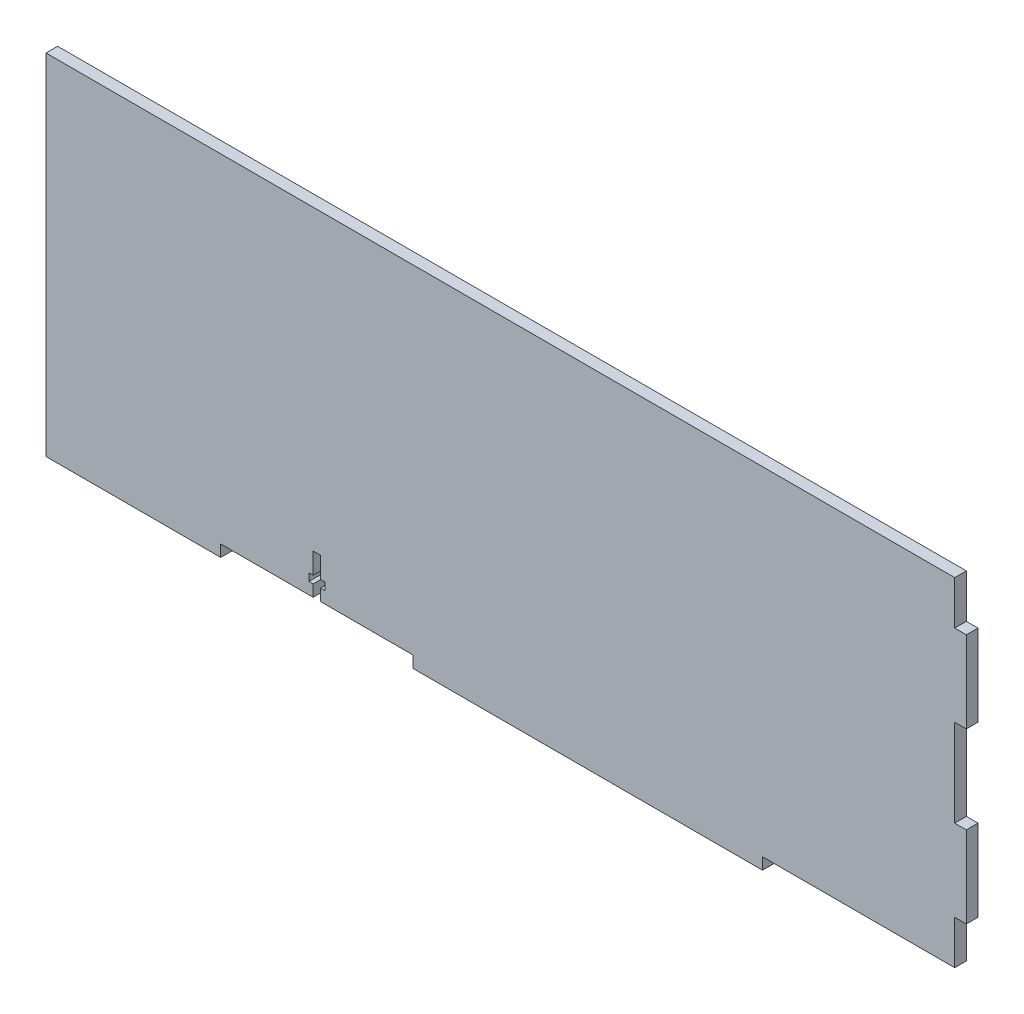
SolidWorks part; units mm, degrees
ref_plane "Alzado" through (0, 0, 0) normal (0, 0, 1) x (1, 0, 0)
ref_plane "Planta" through (0, 0, 0) normal (0, 1, 0) x (1, 0, 0)
ref_plane "Vista lateral" through (0, 0, 0) normal (1, 0, 0) x (0, 0, -1)
sketch "Croquis1" plane through (0, 0, 0) normal (0, 0, 1) x (1, 0, 0)
  line L0 (390, 0) -> (390, -116.2557) construction
  line L1 (0, 0) -> (780, 0)
  line L2 (0, 0) -> (0, 145)
  line L3 (0, 145) -> (780, 145)
  line L4 (780, 0) -> (780, 145)
  line L5 (0, 72.5) -> (-47.1531, 72.5) construction
  line L6 (0, 53.75) -> (-5, 53.75)
  line L7 (0, 126.25) -> (-5, 126.25)
  line L8 (0, 126.25) -> (0, 91.25)
  line L9 (0, 91.25) -> (-5, 91.25)
  line L10 (-5, 126.25) -> (-5, 91.25)
  line L11 (-5, 18.75) -> (-5, 53.75)
  line L12 (0, 18.75) -> (-5, 18.75)
  line L13 (0, 18.75) -> (0, 53.75)
  line L14 (780, 18.75) -> (780, 53.75)
  line L15 (780, 18.75) -> (785, 18.75)
  line L16 (785, 18.75) -> (785, 53.75)
  line L17 (780, 53.75) -> (785, 53.75)
  line L18 (780, 91.25) -> (785, 91.25)
  line L19 (785, 126.25) -> (785, 91.25)
  line L20 (780, 126.25) -> (785, 126.25)
  line L21 (780, 126.25) -> (780, 91.25)
  line L22 (390, 0) -> (315, 0)
  line L27 (82.5, 0) -> (232.5, 0)
  line L28 (82.5, 0) -> (82.5, -5)
  line L29 (82.5, -5) -> (232.5, -5)
  line L30 (232.5, 0) -> (232.5, -5)
  line L31 (315, 0) -> (315, -5)
  line L36 (315, -5) -> (465, -5)
  line L37 (465, -5) -> (465, 0)
  line L38 (465, 0) -> (390, 0)
  line L39 (697.5, -5) -> (547.5, -5)
  line L40 (547.5, 0) -> (547.5, -5)
  line L41 (697.5, 0) -> (547.5, 0)
  line L42 (697.5, 0) -> (697.5, -5)
  dimension "D1" = 780
  dimension "D2" = 145
  dimension "D3" = 18.75
  dimension "D4" = 35
  dimension "D5" = 5
  dimension "D6" = 75
  dimension "D7" = 150
  dimension "D8" = 82.5
  dimension "D9" = 150
  dimension "D10" = 5
  dimension "D11" = 5
extrude "Saliente-Extruir1" add sketch "Croquis1" along normal blind 5 contours L1 L4 L3 L2 | L42 L1 L40 L39 | L36 L37 L1 L31 | L30 L1 L28 L29 | L12 L2 L6 L11 | L16 L17 L14 L15 | L19 L18 L21 L20 | L10 L9 L8 L7
sketch "Croquis2" plane through (0, 0, 5) normal (0, 0, 1) x (1, 0, 0)
  line L0 (273.75, 0) -> (273.75, 79.0587) construction
  line L1 (232.5, 0) -> (315, 0) construction
  line L2 (390, -5) -> (390, 84.2504) construction
  line L3 (315, -5) -> (465, -5) construction
  line L4 (275.35, 0) -> (272.15, 0)
  line L5 (272.15, 0) -> (272.15, 5)
  line L6 (272.15, 5) -> (270.35, 5)
  line L7 (270.35, 5) -> (270.35, 8.2)
  line L8 (270.35, 8.2) -> (272.15, 8.2)
  line L9 (272.15, 8.2) -> (272.15, 17.2)
  line L10 (272.15, 17.2) -> (275.35, 17.2)
  line L11 (275.35, 8.2) -> (275.35, 17.2)
  line L12 (277.15, 8.2) -> (275.35, 8.2)
  line L13 (277.15, 5) -> (277.15, 8.2)
  line L14 (275.35, 5) -> (277.15, 5)
  line L15 (275.35, 0) -> (275.35, 5)
  line L16 (507.85, 8.2) -> (507.85, 17.2)
  line L17 (509.65, 8.2) -> (507.85, 8.2)
  line L18 (509.65, 5) -> (509.65, 8.2)
  line L19 (507.85, 5) -> (509.65, 5)
  line L20 (507.85, 0) -> (507.85, 5)
  line L21 (504.65, 0) -> (507.85, 0)
  line L22 (504.65, 0) -> (504.65, 5)
  line L23 (504.65, 5) -> (502.85, 5)
  line L24 (502.85, 5) -> (502.85, 8.2)
  line L25 (502.85, 8.2) -> (504.65, 8.2)
  line L26 (504.65, 8.2) -> (504.65, 17.2)
  line L27 (507.85, 17.2) -> (504.65, 17.2)
  point P16 (273.75, 17.2)
  dimension "D1" = 1.6
  dimension "D2" = 5
  dimension "D3" = 1.8
  dimension "D4" = 3.2
  dimension "D5" = 1.8
  dimension "D6" = 9
extrude "Cortar-Extruir1" cut sketch "Croquis2" against normal blind 10 contours L10 L11 L12 L13 L14 L15 L4 L5 L6 L7 L8 L9 | L16 L27 L26 L25 L24 L23 L22 L21 L20 L19 L18 L17
sketch "Croquis3" plane through (0, 0, 5) normal (0, 0, 1) x (1, 0, 0)
  line L0 (390, -5) -> (390, 196.9102)
  line L1 (315, -5) -> (465, -5) construction
  line L2 (390, 196.9102) -> (-39.9943, 207.6131)
  line L3 (-39.9943, 207.6131) -> (-47.6477, -99.8669)
  line L4 (-47.6477, -99.8669) -> (0, -99.8669)
  line L5 (0, -99.8669) -> (390, -5)
extrude "Cortar-Extruir2" cut sketch "Croquis3" against normal blind 10
